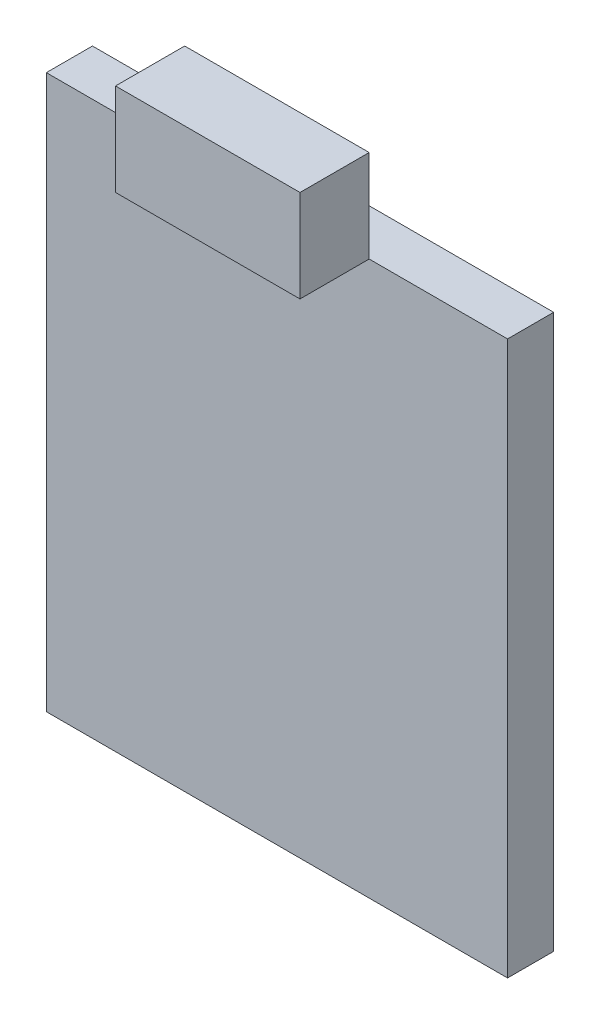
SolidWorks part; units mm, degrees
ref_plane "Front Plane" through (0, 0, 0) normal (0, 0, 1) x (1, 0, 0)
ref_plane "Top Plane" through (0, 0, 0) normal (0, 1, 0) x (1, 0, 0)
ref_plane "Right Plane" through (0, 0, 0) normal (1, 0, 0) x (0, 0, -1)
sketch "Sketch1" plane through (0, 0, 0) normal (0, 0, 1) x (1, 0, 0)
  line L1 (-7.9375, -9.525) -> (7.9375, -9.525)
  line L2 (-7.9375, -9.525) -> (-7.9375, 9.525)
  line L3 (-7.9375, 9.525) -> (7.9375, 9.525)
  line L4 (7.9375, -9.525) -> (7.9375, 9.525)
  line L5 (-7.9375, -9.525) -> (7.9375, 9.525) construction
  line L6 (-7.9375, 9.525) -> (7.9375, -9.525) construction
  point P0 (0, 0)
  dimension "D1" = 19.05
  dimension "D2" = 15.875
extrude "Boss-Extrude1" add sketch "Sketch1" along normal blind 1.5875
sketch "Sketch2" plane through (0, 0, 1.5875) normal (0, 0, 1) x (1, 0, 0)
  line L0 (-7.9375, -9.525) -> (7.9375, -9.525) construction
  line L1 (-3.175, -3.175) -> (3.175, -3.175)
  line L2 (-3.175, -3.175) -> (-3.175, -15.875)
  line L3 (-3.175, -15.875) -> (3.175, -15.875)
  line L4 (3.175, -3.175) -> (3.175, -15.875)
  line L5 (-3.175, -3.175) -> (3.175, -15.875) construction
  line L6 (-3.175, -15.875) -> (3.175, -3.175) construction
  point P0 (0, -9.525)
  dimension "D1" = 6.35
  dimension "D2" = 12.7
extrude "Boss-Extrude2" [suppressed] add sketch "Sketch2" along normal blind 4.7625
sketch "Sketch3" plane through (0, 0, 1.5875) normal (0, 0, 1) x (1, 0, 0)
  line L0 (7.9375, 9.525) -> (-7.9375, 9.525) construction
  line L1 (3.175, 12.7) -> (-3.175, 12.7)
  line L2 (3.175, 12.7) -> (3.175, 9.525)
  line L3 (3.175, 9.525) -> (-3.175, 9.525)
  line L4 (-3.175, 12.7) -> (-3.175, 9.525)
  line L5 (3.175, 12.7) -> (-3.175, 9.525) construction
  line L6 (3.175, 9.525) -> (-3.175, 12.7) construction
  line L7 (0, 11.1125) -> (0, 12.7) construction
  point P0 (0, 11.1125)
  point P9 (0, 9.525)
  dimension "D1" = 6.35
  dimension "D2" = 3.175
extrude "Boss-Extrude3" add sketch "Sketch3" along normal blind 2.3813 separate body
